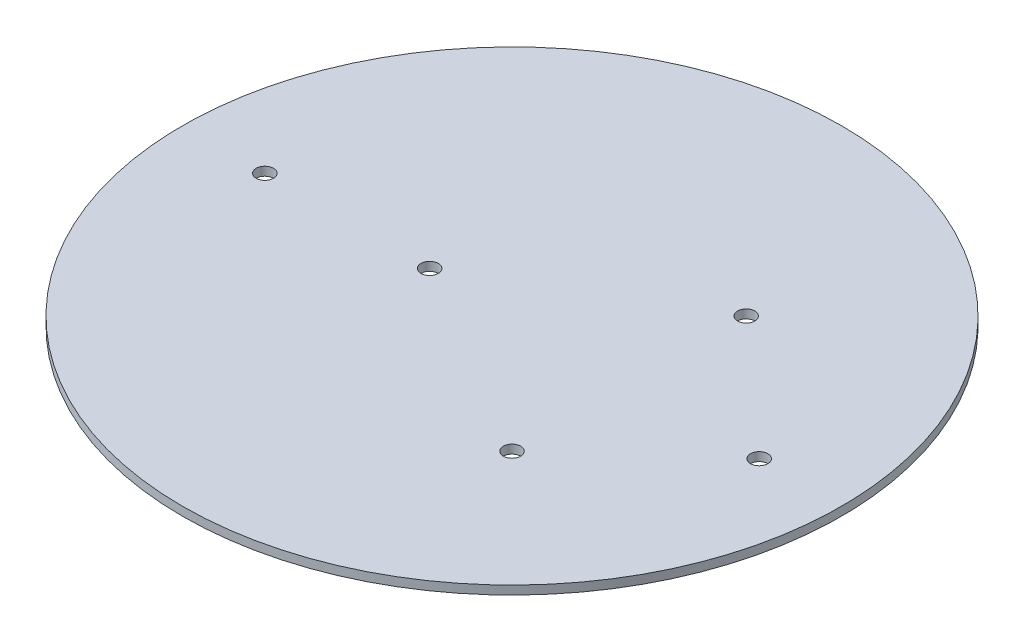
SolidWorks part; units mm, degrees
ref_plane "Front Plane" through (0, 0, 0) normal (0, 0, 1) x (1, 0, 0)
ref_plane "Top Plane" through (0, 0, 0) normal (0, 1, 0) x (1, 0, 0)
ref_plane "Right Plane" through (0, 0, 0) normal (1, 0, 0) x (0, 0, -1)
sketch "Sketch1" plane through (0, 0, 0) normal (0, 1, 0) x (1, 0, 0)
  line L0 (-28.5, 0) -> (28.5, 0) construction
  line L1 (13.5, 0) -> (13.5, 13.5)
  line L2 (13.5, 0) -> (13.5, -13.5)
  circle A1 centre (28.5, 0) radius 1
  circle A2 centre (-28.5, 0) radius 1
  circle A3 centre (13.5, 13.5) radius 1
  circle A4 centre (13.5, -13.5) radius 1
  circle A5 centre (-28.5, 0) radius 6.25 construction
  circle A6 centre (13.5, 13.5) radius 12.5 construction
  circle A7 centre (13.5, -13.5) radius 12.5 construction
  circle A8 centre (28.5, 0) radius 6.25 construction
  circle A9 centre (0, 0) radius 38
  circle A10 centre (-9.5, 0) radius 1
  circle A11 centre (-9.5, 0) radius 12.5 construction
  point P11 (0, 0)
  dimension "D1" = 76
  dimension "D3" = 2
  dimension "D4" = 13.5
  dimension "D5" = 2
  dimension "D6" = 12.5
  dimension "D7" = 25
  dimension "D8" = 2
  dimension "D9" = 25
  dimension "D2" = 57
  dimension "D10" = 9.5
  dimension "D11" = 13.5
extrude "Boss-Extrude1" add sketch "Sketch1" against normal blind 1
